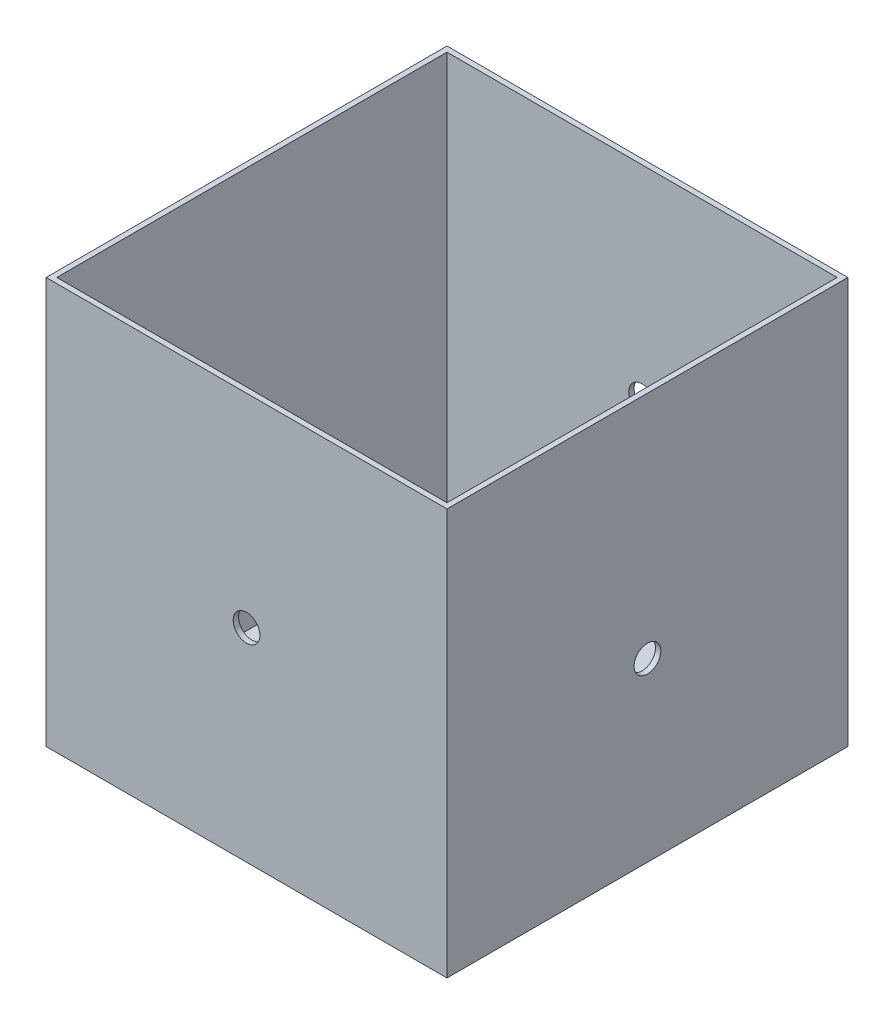
SolidWorks part; units mm, degrees
material "Polyethylene Cross-Linked"
ref_plane "Front Plane" through (0, 0, 0) normal (0, 0, 1) x (1, 0, 0)
ref_plane "Top Plane" through (0, 0, 0) normal (0, 1, 0) x (1, 0, 0)
ref_plane "Right Plane" through (0, 0, 0) normal (1, 0, 0) x (0, 0, -1)
sketch "Sketch1" plane through (0, 0, 0) normal (0, 1, 0) x (1, 0, 0)
  line L1 (-75, -75) -> (75, -75)
  line L2 (-75, -75) -> (-75, 75)
  line L3 (-75, 75) -> (75, 75)
  line L4 (75, -75) -> (75, 75)
  line L5 (-75, -75) -> (75, 75) construction
  line L6 (-75, 75) -> (75, -75) construction
  point P0 (0, 0)
  dimension "D1" = 150
  dimension "D2" = 150
extrude "Boss-Extrude1" add sketch "Sketch1" along normal blind 0.5
sketch "Sketch2" plane through (0, 0.5, 0) normal (0, 1, 0) x (1, 0, 0)
  line L0 (-75, 75) -> (-75, -75) construction
  line L1 (73, -73) -> (-73, -73)
  line L2 (73, -73) -> (73, 73)
  line L3 (73, 73) -> (-73, 73)
  line L4 (-73, -73) -> (-73, 73)
  line L5 (73, -73) -> (-73, 73) construction
  line L6 (73, 73) -> (-73, -73) construction
  line L7 (-75, -75) -> (75, -75) construction
  line L9 (75, -75) -> (-75, -75)
  line L10 (75, -75) -> (75, 75)
  line L11 (75, 75) -> (-75, 75)
  line L12 (-75, -75) -> (-75, 75)
  line L13 (75, -75) -> (-75, 75) construction
  line L14 (75, 75) -> (-75, -75) construction
  point P0 (0, 0)
  point P10 (0, -73)
  point P11 (0, 0)
  dimension "D1" = 2
  dimension "D2" = 2
extrude "Boss-Extrude2" add sketch "Sketch2" along normal blind 15
sketch "Sketch6" plane through (0, 15.5, 0) normal (0, 1, 0) x (1, 0, 0)
  line L1 (-75, 75) -> (75, 75)
  line L2 (-75, 75) -> (-75, -75)
  line L3 (-75, -75) -> (75, -75)
  line L4 (75, 75) -> (75, -75)
  line L5 (-75, 75) -> (75, -75) construction
  line L6 (-75, -75) -> (75, 75) construction
  line L7 (-73, 73) -> (73, 73)
  line L8 (-73, 73) -> (-73, -73)
  line L9 (-73, -73) -> (73, -73)
  line L10 (73, 73) -> (73, -73)
  line L11 (-73, 73) -> (73, -73) construction
  line L12 (-73, -73) -> (73, 73) construction
  point P0 (0, 0)
  point P7 (0, 0)
extrude "Boss-Extrude4" add sketch "Sketch6" along normal blind 135
sketch "Sketch7" plane through (0, 0, 0) normal (0, -1, 0) x (1, 0, 0)
  line L1 (75, 75) -> (-75, 75)
  line L2 (75, 75) -> (75, -75)
  line L3 (75, -75) -> (-75, -75)
  line L4 (-75, 75) -> (-75, -75)
  line L5 (75, 75) -> (-75, -75) construction
  line L6 (75, -75) -> (-75, 75) construction
  point P0 (0, 0)
extrude "Boss-Extrude5" add sketch "Sketch7" along normal blind 1.5
sketch "Sketch8" plane through (0, 0, -75) normal (0, 0, -1) x (-1, 0, 0)
  circle A0 centre (0, 74.5) radius 5
  dimension "D1" = 10
extrude "Cut-Extrude1" cut sketch "Sketch8" against normal through all
sketch "Sketch9" plane through (-75, 0, 0) normal (-1, 0, 0) x (0, 0, 1)
  line L0 (-75, 74.5) -> (37.134, 74.5) construction
  line L1 (-75, 150.5) -> (-75, -1.5) construction
  line L2 (0, 0) -> (0, 64.5) construction
  circle A0 centre (0, 64.5) radius 5
  dimension "D2" = 10
  dimension "D1" = 10
extrude "Cut-Extrude2" cut sketch "Sketch9" against normal through all
